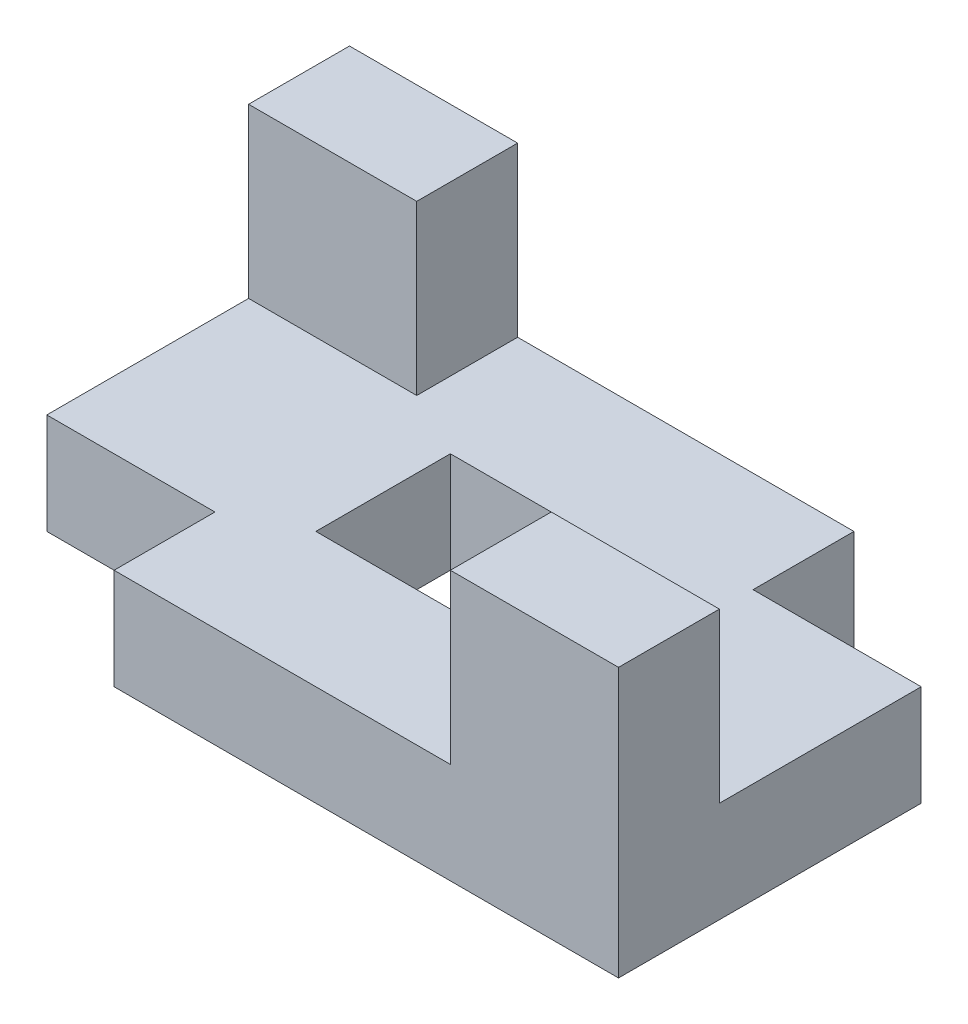
SolidWorks part; units mm, degrees
ref_plane "Front Plane" through (0, 0, 0) normal (0, 0, 1) x (1, 0, 0)
ref_plane "Top Plane" through (0, 0, 0) normal (0, 1, 0) x (1, 0, 0)
ref_plane "Right Plane" through (0, 0, 0) normal (1, 0, 0) x (0, 0, -1)
sketch "Sketch1" plane through (0, 0, 0) normal (0, 1, 0) x (1, 0, 0)
  line L1 (-50, 30) -> (50, 30)
  line L2 (-50, 30) -> (-50, -30)
  line L3 (-50, -30) -> (50, -30)
  line L4 (50, 30) -> (50, -30)
  dimension "D1" = 100
  dimension "D2" = 60
  dimension "D3" = 50
  dimension "D4" = 30
extrude "Boss-Extrude1" add sketch "Sketch1" along normal blind 15
sketch "Sketch2" plane through (0, 15, 0) normal (0, 1, 0) x (1, 0, 0)
  line L1 (-50, 30) -> (-25, 30)
  line L2 (-50, 30) -> (-50, 15)
  line L3 (-50, 15) -> (-25, 15)
  line L4 (-25, 30) -> (-25, 15)
  line L5 (50, -30) -> (25, -30)
  line L6 (50, -30) -> (50, -15)
  line L7 (50, -15) -> (25, -15)
  line L8 (25, -30) -> (25, -15)
  dimension "D1" = 25
  dimension "D2" = 15
extrude "Boss-Extrude2" add sketch "Sketch2" along normal blind 25
sketch "Sketch3" plane through (0, 15, 0) normal (0, 1, 0) x (1, 0, 0)
  line L1 (-50, -30) -> (-25, -30)
  line L2 (-50, -30) -> (-50, -15)
  line L3 (-50, -15) -> (-25, -15)
  line L4 (-25, -30) -> (-25, -15)
  line L5 (50, 30) -> (25, 30)
  line L6 (50, 30) -> (50, 15)
  line L7 (50, 15) -> (25, 15)
  line L8 (25, 30) -> (25, 15)
  dimension "D1" = 25
  dimension "D2" = 15
extrude "Cut-Extrude1" cut sketch "Sketch3" against normal blind 15
sketch "Sketch4" plane through (0, 15, 0) normal (0, 1, 0) x (1, 0, 0)
  line L0 (-25, -30) -> (25, -30) construction
  line L1 (-15, 10) -> (15, 10)
  line L2 (-15, 10) -> (-15, -10)
  line L3 (-15, -10) -> (15, -10)
  line L4 (15, 10) -> (15, -10)
  line L5 (-50, 15) -> (-50, -15) construction
  dimension "D1" = 30
  dimension "D2" = 20
  dimension "D3" = 20
  dimension "D4" = 35
extrude "Cut-Extrude2" cut sketch "Sketch4" against normal blind 15
